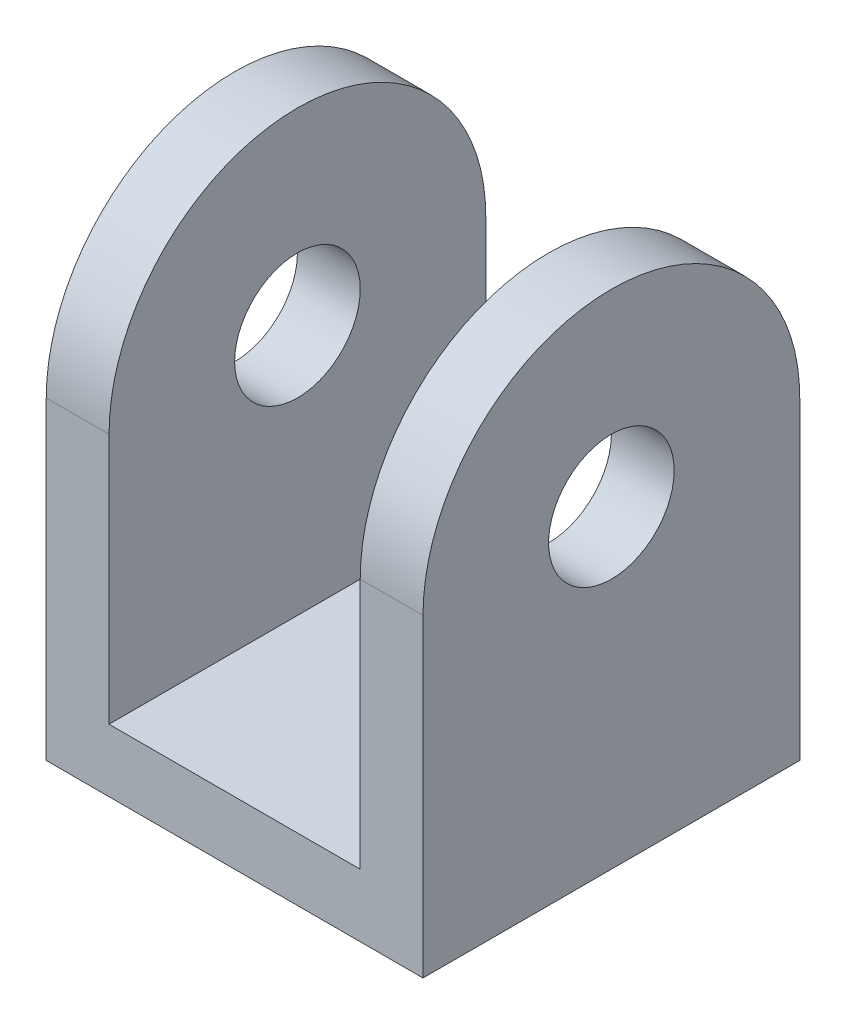
SolidWorks part; units mm, degrees
ref_plane "前基準面" through (0, 0, 0) normal (0, 0, 1) x (1, 0, 0)
ref_plane "上基準面" through (0, 0, 0) normal (0, 1, 0) x (1, 0, 0)
ref_plane "右基準面" through (0, 0, 0) normal (1, 0, 0) x (0, 0, -1)
sketch "草圖2" plane through (0, 0, 0) normal (0, 0, 1) x (1, 0, 0)
  line L0 (0, 0) -> (60, 0)
  line L1 (60, 0) -> (60, 50)
  line L2 (60, 50) -> (50, 50)
  line L3 (50, 50) -> (50, 10)
  line L4 (50, 10) -> (10, 10)
  line L5 (10, 10) -> (10, 50)
  line L6 (10, 50) -> (0, 50)
  line L7 (0, 50) -> (0, 0)
  dimension "D1" = 50
  dimension "D2" = 60
  dimension "D3" = 10
  dimension "D4" = 10
  dimension "D5" = 10
  dimension "D6" = 50
extrude "填料-伸長1" add sketch "草圖2" along normal blind 60
sketch "草圖3" plane through (60, 0, 0) normal (1, 0, 0) x (0, 0, -1)
  line L0 (-60, 50) -> (0, 50) construction
  line L3 (0, 0) -> (0, 50) construction
  circle A0 centre (-30, 50) radius 10
  dimension "D1" = 20
  dimension "D2" = 30
extrude "除料-伸長1" cut sketch "草圖3" against normal through all contours A0
sketch "草圖8" plane through (0, 0, 0) normal (1, 0, 0) x (0, 0, -1)
  line L0 (-60, 0) -> (0, 0) construction
  circle A0 centre (-30, 50) radius 30
  circle A2 centre (-30, 50) radius 10
  dimension "D1" = 60
  dimension "D5" = 20
  dimension "D2" = 50
  dimension "D3" = 50
  dimension "D4" = 30
extrude "填料-伸長5" add sketch "草圖8" along normal blind 60
sketch "草圖10" plane through (0, 0, 60) normal (0, 0, 1) x (1, 0, 0)
  line L0 (60, 80) -> (0, 80) construction
  line L1 (10, 10) -> (50, 10)
  line L2 (10, 10) -> (10, 80)
  line L3 (10, 80) -> (50, 80)
  line L4 (50, 10) -> (50, 80)
  line L5 (60, 0) -> (60, 50) construction
  line L6 (0, 50) -> (0, 0) construction
  line L7 (0, 0) -> (60, 0) construction
  point P11 (0, 25)
  dimension "D1" = 10
  dimension "D2" = 10
  dimension "D3" = 10
extrude "除料-伸長3" cut sketch "草圖10" against normal blind 60
